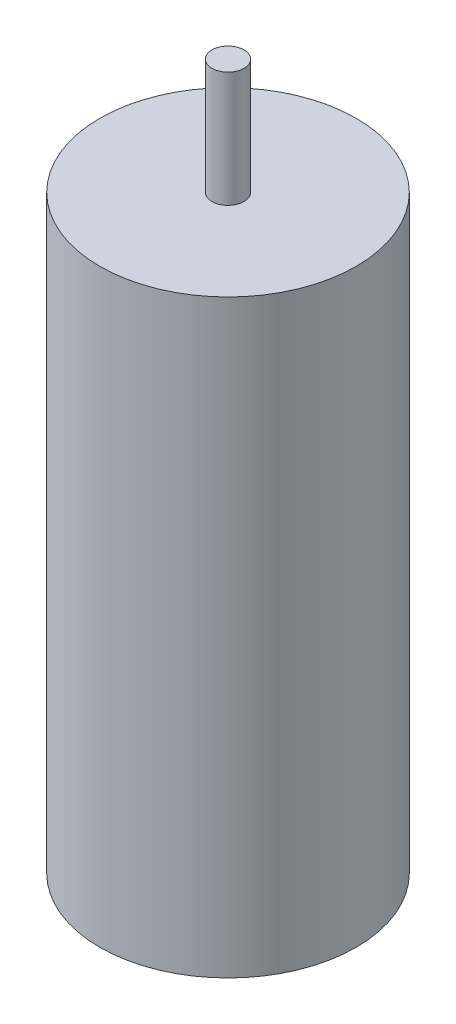
SolidWorks part; units mm, degrees
ref_plane "Front Plane" through (0, 0, 0) normal (0, 0, 1) x (1, 0, 0)
ref_plane "Top Plane" through (0, 0, 0) normal (0, 1, 0) x (1, 0, 0)
ref_plane "Right Plane" through (0, 0, 0) normal (1, 0, 0) x (0, 0, -1)
sketch "Sketch4" plane through (0, 0, 0) normal (0, 0, 1) x (1, 0, 0)
  line L0 (0, 88.1063) -> (0, -47.5917) construction
  line L1 (0, -40.3847) -> (20, -40.3847)
  line L2 (20, -40.3847) -> (20, 51.6153)
  line L3 (20, 51.6153) -> (2.5, 51.6153)
  line L4 (2.5, 51.6153) -> (2.5, 69.6153)
  line L5 (2.5, 69.6153) -> (0, 69.6153)
  line L6 (0, -40.3847) -> (0, 69.6153)
  dimension "D1" = 20
  dimension "D2" = 20
  dimension "D3" = 2.5
  dimension "D4" = 92
revolve "Revolve1" add sketch "Sketch4" angle 360 about L0
